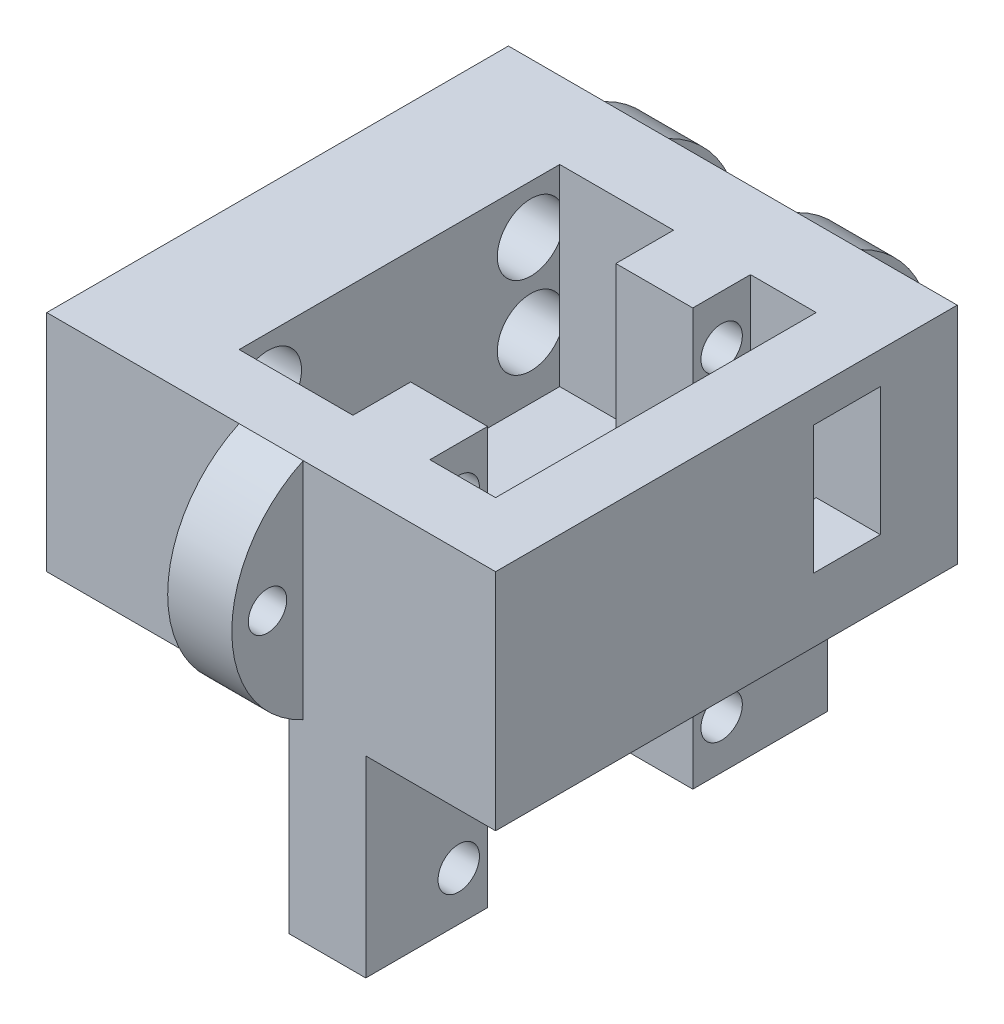
SolidWorks part; units mm, degrees
ref_plane "Front Plane" through (0, 0, 0) normal (0, 0, 1) x (1, 0, 0)
ref_plane "Top Plane" through (0, 0, 0) normal (0, 1, 0) x (1, 0, 0)
ref_plane "Right Plane" through (0, 0, 0) normal (1, 0, 0) x (0, 0, -1)
sketch "Sketch1" plane through (0, 0, 0) normal (0, 1, 0) x (1, 0, 0)
  line L1 (-44.45, -45.72) -> (44.45, -45.72)
  line L2 (-44.45, -45.72) -> (-44.45, 45.72)
  line L3 (-44.45, 45.72) -> (44.45, 45.72)
  line L4 (44.45, -45.72) -> (44.45, 45.72)
  line L5 (-44.45, -45.72) -> (44.45, 45.72) construction
  line L6 (-44.45, 45.72) -> (44.45, -45.72) construction
  point P0 (0, 0)
  dimension "D1" = 88.9
  dimension "D2" = 91.44
extrude "Boss-Extrude1" add sketch "Sketch1" along normal blind 44.45
sketch "Sketch2" plane through (0, 44.45, 0) normal (0, 1, 0) x (1, 0, 0)
  line L0 (44.45, -45.72) -> (44.45, 45.72) construction
  line L1 (-44.45, -45.72) -> (44.45, -45.72) construction
  line L2 (-44.45, 45.72) -> (-44.45, -45.72) construction
  line L3 (44.45, 45.72) -> (-44.45, 45.72) construction
  line L4 (44.45, -45.72) -> (44.45, 45.72)
  line L5 (-44.45, -45.72) -> (44.45, -45.72)
  line L6 (-44.45, 45.72) -> (-44.45, -45.72)
  line L7 (44.45, 45.72) -> (-44.45, 45.72)
  line L9 (-19.05, -33.02) -> (31.75, -33.02)
  line L10 (-19.05, -33.02) -> (-19.05, 30.48)
  line L11 (-19.05, 30.48) -> (31.75, 30.48)
  line L12 (31.75, -33.02) -> (31.75, 30.48)
  line L13 (-19.05, -33.02) -> (31.75, 30.48) construction
  line L14 (-19.05, 30.48) -> (31.75, -33.02) construction
  line L15 (3.4969, -33.02) -> (18.7369, -33.02)
  line L16 (3.4969, -33.02) -> (3.4969, -21.59)
  line L17 (3.4969, -21.59) -> (18.7369, -21.59)
  line L18 (18.7369, -33.02) -> (18.7369, -21.59)
  line L20 (3.4969, 30.48) -> (18.7369, 30.48)
  line L21 (3.4969, 30.48) -> (3.4969, 19.05)
  line L22 (3.4969, 19.05) -> (18.7369, 19.05)
  line L23 (18.7369, 30.48) -> (18.7369, 19.05)
  point P3 (6.35, -1.27)
  dimension "D1" = 63.5
  dimension "D2" = 50.8
  dimension "D3" = 25.4
  dimension "D4" = 12.7
  dimension "D5" = 15.24
  dimension "D6" = 11.43
extrude "Cut-Extrude1" cut sketch "Sketch2" against normal blind 38.1 contours L11 L23 L22 L21 L10 L9 L16 L17 L18 L12
sketch "Sketch3" plane through (3.4969, 0, 0) normal (-1, 0, 0) x (0, 0, 1)
  line L0 (-24.765, 6.35) -> (-24.765, 44.45)
  line L1 (27.305, 6.35) -> (27.305, 44.45)
  line L4 (-19.05, 44.45) -> (-30.48, 44.45)
  line L5 (-30.48, 44.45) -> (-30.48, 6.35)
  line L6 (-30.48, 6.35) -> (-19.05, 6.35)
  line L7 (-19.05, 6.35) -> (-19.05, 44.45)
  line L8 (-19.05, 44.45) -> (-30.48, 44.45)
  line L9 (-30.48, 44.45) -> (-30.48, 6.35)
  line L10 (-30.48, 6.35) -> (-19.05, 6.35)
  line L11 (-19.05, 6.35) -> (-19.05, 44.45)
  line L12 (33.02, 44.45) -> (21.59, 44.45)
  line L13 (21.59, 44.45) -> (21.59, 6.35)
  line L14 (21.59, 6.35) -> (33.02, 6.35)
  line L15 (33.02, 6.35) -> (33.02, 44.45)
  line L16 (33.02, 44.45) -> (21.59, 44.45)
  line L17 (21.59, 44.45) -> (21.59, 6.35)
  line L18 (21.59, 6.35) -> (33.02, 6.35)
  line L19 (33.02, 6.35) -> (33.02, 44.45)
  circle A0 centre (-24.765, 34.798) radius 4.1
  circle A1 centre (-24.765, 18.542) radius 4.1
  circle A3 centre (27.305, 18.542) radius 4.1
  circle A4 centre (27.305, 34.798) radius 4.1
  dimension "D1" = 8.2
  dimension "D4" = 12.192
  dimension "D5" = 9.652
  dimension "D2" = 0
  dimension "D3" = 0
extrude "Cut-Extrude2" cut sketch "Sketch3" against normal up to surface (15.24 mm away) contours L0 A1 | L0 A1 | L0 A0 | L0 A0 | L1 A3 | L1 A3 | L1 A4 | L1 A4 up to face at (18.7369, 25.4, -24.765)
sketch "Sketch4" plane through (-44.45, 0, 0) normal (-1, 0, 0) x (0, 0, 1)
  circle A16 centre (-24.765, 18.542) radius 6.64
  circle A17 centre (-24.765, 18.542) radius 6.64
  circle A19 centre (-24.765, 34.798) radius 6.64
  circle A20 centre (-24.765, 34.798) radius 6.64
  circle A22 centre (27.305, 18.542) radius 6.64
  circle A23 centre (27.305, 18.542) radius 6.64
  circle A25 centre (27.305, 34.798) radius 6.64
  circle A26 centre (27.305, 34.798) radius 6.64
  dimension "D1" = 2.54
  dimension "D2" = 2.54
  dimension "D3" = 2.54
  dimension "D4" = 2.54
extrude "Cut-Extrude3" cut sketch "Sketch4" against normal up to surface (25.4 mm away) up to face at (-19.05, 25.4, 1.27)
sketch "Sketch5" plane through (31.75, 0, 0) normal (-1, 0, 0) x (0, 0, 1)
  line L1 (-30.48, 12.7) -> (-17.2701, 12.7)
  line L2 (-30.48, 12.7) -> (-30.48, 38.1)
  line L3 (-30.48, 38.1) -> (-17.2701, 38.1)
  line L4 (33.02, 44.45) -> (-30.48, 44.45)
  line L5 (-30.48, 44.45) -> (-30.48, 6.35)
  line L6 (-30.48, 6.35) -> (33.02, 6.35)
  line L7 (33.02, 6.35) -> (33.02, 44.45)
  line L8 (33.02, 44.45) -> (-30.48, 44.45)
  line L9 (-30.48, 44.45) -> (-30.48, 6.35)
  line L10 (-30.48, 6.35) -> (33.02, 6.35)
  line L11 (33.02, 6.35) -> (33.02, 44.45)
  line L12 (-17.2701, 12.7) -> (-17.2701, 38.1)
  dimension "D2" = 0
  dimension "D3" = 25.4
  dimension "D4" = 6.35
  dimension "D1" = 0
extrude "Cut-Extrude4" cut sketch "Sketch5" against normal up to surface (12.7 mm away) contours L2 L1 L12 L3 up to face at (44.45, 22.225, 0)
sketch "Sketch8" plane through (0, 0, 0) normal (1, 0, 0) x (0, 0, -1)
  line L0 (45.72, 22.225) -> (59.6781, 22.225)
  line L4 (-45.72, 0) -> (45.72, 0)
  line L5 (-45.72, 44.45) -> (-45.72, 0)
  line L6 (45.72, 44.45) -> (-45.72, 44.45)
  line L7 (45.72, 0) -> (45.72, 44.45)
  line L11 (45.72, 0) -> (45.72, 44.45)
  arc A0 (45.72, 0) -> (45.72, 44.45) centre (35.005, 22.225) ccw
  circle A1 centre (52.6991, 22.225) radius 3.8522
  point P4 (59.6781, 22.225)
  point P6 (45.72, 22.225)
  dimension "D2" = 13.9581
  dimension "D1" = 0
extrude "Boss-Extrude2" add sketch "Sketch8" along normal blind 25.4 and the other way blind 25.4 contours A1 L0 L11 A0 | A1 L0 A0 L11
sketch "Sketch9" plane through (0, 0, 0) normal (0, 1, 0) x (1, 0, 0)
  line L0 (-25.4, 45.72) -> (25.4, 45.72) construction
  line L4 (-25.4, 45.72) -> (25.4, 45.72)
  line L5 (0, 63.9416) -> (0, 45.72)
  line L6 (-12.7, 45.72) -> (12.7, 45.72)
  line L7 (-12.7, 45.72) -> (-12.7, 63.9416)
  line L8 (-12.7, 63.9416) -> (12.7, 63.9416)
  line L9 (12.7, 45.72) -> (12.7, 63.9416)
  dimension "D1" = 12.7
  dimension "D2" = 12.7
extrude "Cut-Extrude6" cut sketch "Sketch9" against normal blind 2.54 and the other way blind 45.72 contours L8 L7 L4 L5 | L4 L9 L8 L5
sketch "Sketch10" plane through (0, 0, 0) normal (1, 0, 0) x (0, 0, -1)
  line L0 (-45.72, 44.45) -> (-45.72, 0) construction
  line L1 (-45.72, 44.45) -> (-45.72, 0)
  line L2 (-45.72, 22.225) -> (-59.8665, 22.225)
  arc A1 (-45.72, 44.45) -> (-45.72, 0) centre (-35.3349, 22.225) ccw
  circle A2 centre (-52.7933, 22.225) radius 3.81
  dimension "D1" = 7.62
extrude "Boss-Extrude4" add sketch "Sketch10" along normal blind 6.35 and the other way blind 6.35 contours A2 L2 L1 A1 | A2 L2 A1 L1
sketch "Sketch11" plane through (0, 0, 0) normal (0, -1, 0) x (1, 0, 0)
  line L0 (18.7369, 33.02) -> (18.7369, 21.59) construction
  line L1 (3.4969, 21.59) -> (18.7369, 21.59) construction
  line L2 (3.4969, 33.02) -> (3.4969, 21.59) construction
  line L3 (18.7369, -30.48) -> (18.7369, -19.05) construction
  line L4 (3.4969, -19.05) -> (18.7369, -19.05) construction
  line L5 (3.4969, -30.48) -> (3.4969, -19.05) construction
  line L6 (18.7369, 33.02) -> (18.7369, 21.59)
  line L7 (3.4969, 21.59) -> (18.7369, 21.59)
  line L8 (3.4969, 33.02) -> (3.4969, 21.59)
  line L9 (18.7369, -30.48) -> (18.7369, -19.05)
  line L10 (3.4969, -19.05) -> (18.7369, -19.05)
  line L11 (3.4969, -30.48) -> (3.4969, -19.05)
  line L14 (18.7369, 33.02) -> (18.7369, 45.72)
  line L15 (6.35, 45.72) -> (44.45, 45.72) construction
  line L16 (3.4969, 33.02) -> (3.4969, 45.72)
  line L17 (-6.35, 45.72) -> (6.35, 45.72) construction
  line L18 (18.7369, -30.48) -> (18.7369, -45.72)
  line L19 (12.7, -45.72) -> (25.4, -45.72) construction
  line L20 (3.4969, -30.48) -> (3.4969, -45.72)
  line L21 (-12.7, -45.72) -> (12.7, -45.72) construction
  line L22 (18.7369, -45.72) -> (3.4969, -45.72)
  line L23 (18.7369, 45.72) -> (3.4969, 45.72)
extrude "Boss-Extrude6" add sketch "Sketch11" along normal blind 38.1
sketch "Sketch12" plane through (18.7369, 0, 0) normal (1, 0, 0) x (0, 0, -1)
  line L0 (45.72, 0) -> (19.05, 0) construction
  line L1 (45.72, -38.1) -> (19.05, -38.1) construction
  circle A0 centre (24.765, -12.192) radius 4.1
  circle A1 centre (24.765, -28.448) radius 4.1
  circle A2 centre (24.765, 18.542) radius 4.1 construction
  circle A3 centre (24.765, 18.542) radius 4.1
  circle A4 centre (24.765, 34.798) radius 4.1 construction
  circle A5 centre (24.765, 34.798) radius 4.1
  circle A6 centre (-27.305, 18.542) radius 4.1 construction
  circle A7 centre (-27.305, 34.798) radius 4.1 construction
  circle A8 centre (-27.305, 18.542) radius 4.1
  circle A9 centre (-27.305, 34.798) radius 4.1
  circle A10 centre (-27.305, -12.192) radius 4.1
  circle A11 centre (-27.305, -28.448) radius 4.1
  dimension "D1" = 12.192
  dimension "D2" = 9.652
extrude "Cut-Extrude7" cut sketch "Sketch12" against normal through all contours A0 | A1 | A11 | A10
